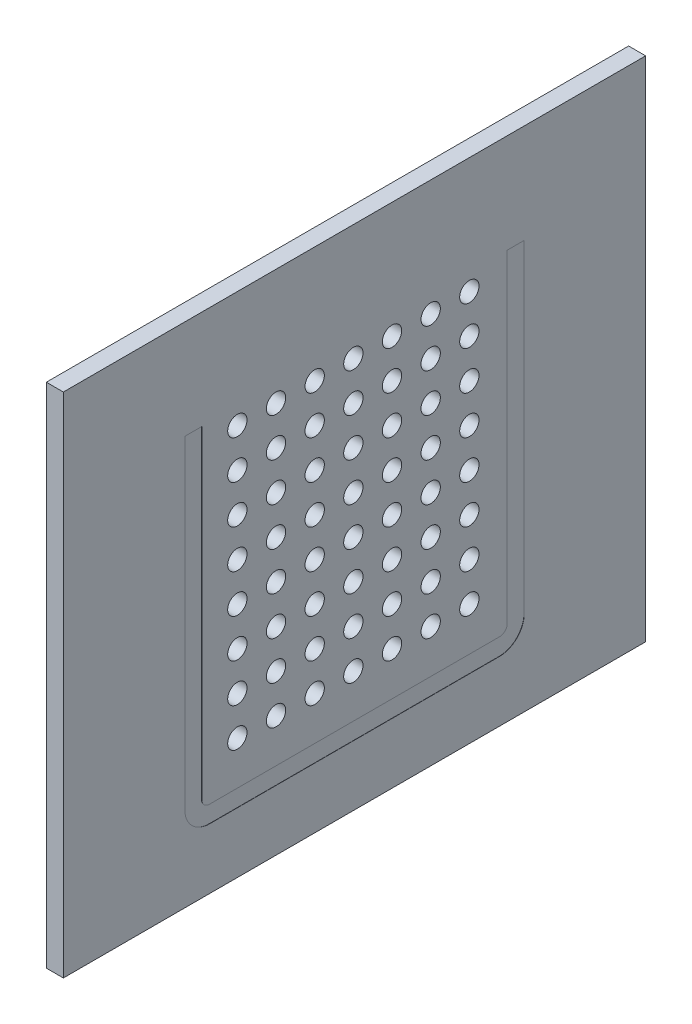
SolidWorks part; units mm, degrees
material "Acrylic (Medium-high impact)"
ref_plane "Front Plane" through (0, 0, 0) normal (0, 0, 1) x (1, 0, 0)
ref_plane "Top Plane" through (0, 0, 0) normal (0, 1, 0) x (1, 0, 0)
ref_plane "Right Plane" through (0, 0, 0) normal (1, 0, 0) x (0, 0, -1)
sketch "Sketch1" plane through (0, 0, 0) normal (1, 0, 0) x (0, 0, -1)
  line L1 (-95.631, 83.3438) -> (95.631, 83.3438)
  line L2 (-95.631, 83.3438) -> (-95.631, -83.3437)
  line L3 (-95.631, -83.3437) -> (95.631, -83.3437)
  line L4 (95.631, 83.3438) -> (95.631, -83.3437)
  line L5 (-95.631, 83.3438) -> (95.631, -83.3437) construction
  line L6 (-95.631, -83.3437) -> (95.631, 83.3438) construction
  point P0 (0, 0)
  dimension "D1" = 191.262
  dimension "D2" = 166.6875
extrude "Boss-Extrude1" add sketch "Sketch1" along normal blind 5.588
hole_wizard "#10 Clearance Hole1" [suppressed] positions "Sketch4" profile "Sketch3" hole size "#10" standard "ANSI Inch"
sketch "Sketch4" plane through (5.588, 0, 0) normal (1, 0, 0) x (0, 0, -1)
  line L1 (-48.514, 35.814) -> (23.114, 35.814) construction
  line L2 (-48.514, 35.814) -> (-48.514, -35.814) construction
  line L3 (-48.514, -35.814) -> (23.114, -35.814) construction
  line L4 (23.114, 35.814) -> (23.114, -35.814) construction
  line L5 (-48.514, 35.814) -> (23.114, -35.814) construction
  line L7 (-12.7, 0) -> (0, 0) construction
  point P1 (-48.514, 35.814)
  point P2 (23.114, -35.814)
  point P153 (-48.514, -35.814)
  point P154 (23.114, 35.814)
  dimension "D1" = 71.628
  dimension "D2" = 12.7
sketch "Sketch3" plane through (5.588, 35.814, 48.514) normal (0, 1, 0) x (0, 0, -1)
  line L0 (0, 0) -> (0, 14.2338)
  line L1 (0, 14.2338) -> (2.5527, 12.7)
  line L2 (2.5527, 12.7) -> (2.5527, 0)
  line L5 (2.5527, 0) -> (0, 0)
  line L10 (0, 14.2338) -> (-2.5527, 12.7) construction
  line L11 (0, -6.35) -> (0, 107.95) construction
  dimension "Hole Dia." = 5.1054
  dimension "Hole Depth" = 12.7
  dimension "Drill Angle" = 118
sketch "Sketch5" [suppressed] plane through (5.588, 0, 0) normal (1, 0, 0) x (0, 0, -1)
  line L0 (-48.514, 35.814) -> (23.114, -35.814) construction
  line L2 (-39.6875, 33.3375) -> (14.2875, 33.3375)
  line L3 (-46.0375, 26.9875) -> (-46.0375, -26.9875)
  line L4 (-39.6875, -33.3375) -> (14.2875, -33.3375)
  line L5 (20.6375, 26.9875) -> (20.6375, -26.9875)
  line L6 (-46.0375, 33.3375) -> (20.6375, -33.3375) construction
  line L7 (-46.0375, -33.3375) -> (20.6375, 33.3375) construction
  arc A0 (14.2875, -33.3375) -> (20.6375, -26.9875) centre (14.2875, -26.9875) ccw
  arc A1 (-46.0375, -26.9875) -> (-39.6875, -33.3375) centre (-39.6875, -26.9875) ccw
  arc A2 (-39.6875, 33.3375) -> (-46.0375, 26.9875) centre (-39.6875, 26.9875) ccw
  arc A3 (14.2875, 33.3375) -> (20.6375, 26.9875) centre (14.2875, 26.9875) cw
  point P4 (-12.7, 0)
  dimension "D2" = 6.35
  dimension "D1" = 66.675
extrude "Cut-Extrude1" [suppressed] cut sketch "Sketch5" against normal up to next
sketch "Sketch6" plane through (5.588, 0, 0) normal (1, 0, 0) x (0, 0, -1)
  line L0 (95.631, 83.3438) -> (-95.631, 83.3438) construction
  line L1 (-95.631, 83.3438) -> (-95.631, -83.3437) construction
  circle A0 centre (-38.481, 45.2438) radius 3.175
  dimension "D1" = 38.1
  dimension "D2" = 57.15
  dimension "D3" = 6.35
extrude "Cut-Extrude2" cut sketch "Sketch6" against normal up to next
pattern_linear "LPattern1" count 7 spacing 12.7 along (0, 0, -1) count 8 spacing 12.7 along (0, -1, 0) of "Cut-Extrude2"
sketch "Sketch7" plane through (5.588, 0, 0) normal (1, 0, 0) x (0, 0, -1)
  line L0 (-55.753, -55.372) -> (-55.753, 50.8)
  line L1 (-55.753, 50.8) -> (-50.165, 50.8)
  line L2 (-50.165, 50.8) -> (-50.165, -55.372)
  line L3 (-47.625, -57.912) -> (47.625, -57.912)
  line L4 (50.165, -55.372) -> (50.165, 50.8)
  line L5 (50.165, 50.8) -> (55.753, 50.8)
  line L6 (55.753, 50.8) -> (55.753, -55.372)
  line L7 (47.625, -63.5) -> (-47.625, -63.5)
  line L8 (0, 0) -> (0, -63.5) construction
  arc A0 (-50.165, -55.372) -> (-47.625, -57.912) centre (-47.625, -55.372) ccw
  arc A1 (47.625, -57.912) -> (50.165, -55.372) centre (47.625, -55.372) ccw
  arc A2 (55.753, -55.372) -> (47.625, -63.5) centre (47.625, -55.372) cw
  arc A3 (-47.625, -63.5) -> (-55.753, -55.372) centre (-47.625, -55.372) cw
  dimension "D3" = 2.54
  dimension "D1" = 100.33
  dimension "D2" = 114.3
  dimension "D4" = 5.588
  dimension "D5" = 63.5
extrude "Cut-Extrude3" cut sketch "Sketch7" against normal blind 0.0762
